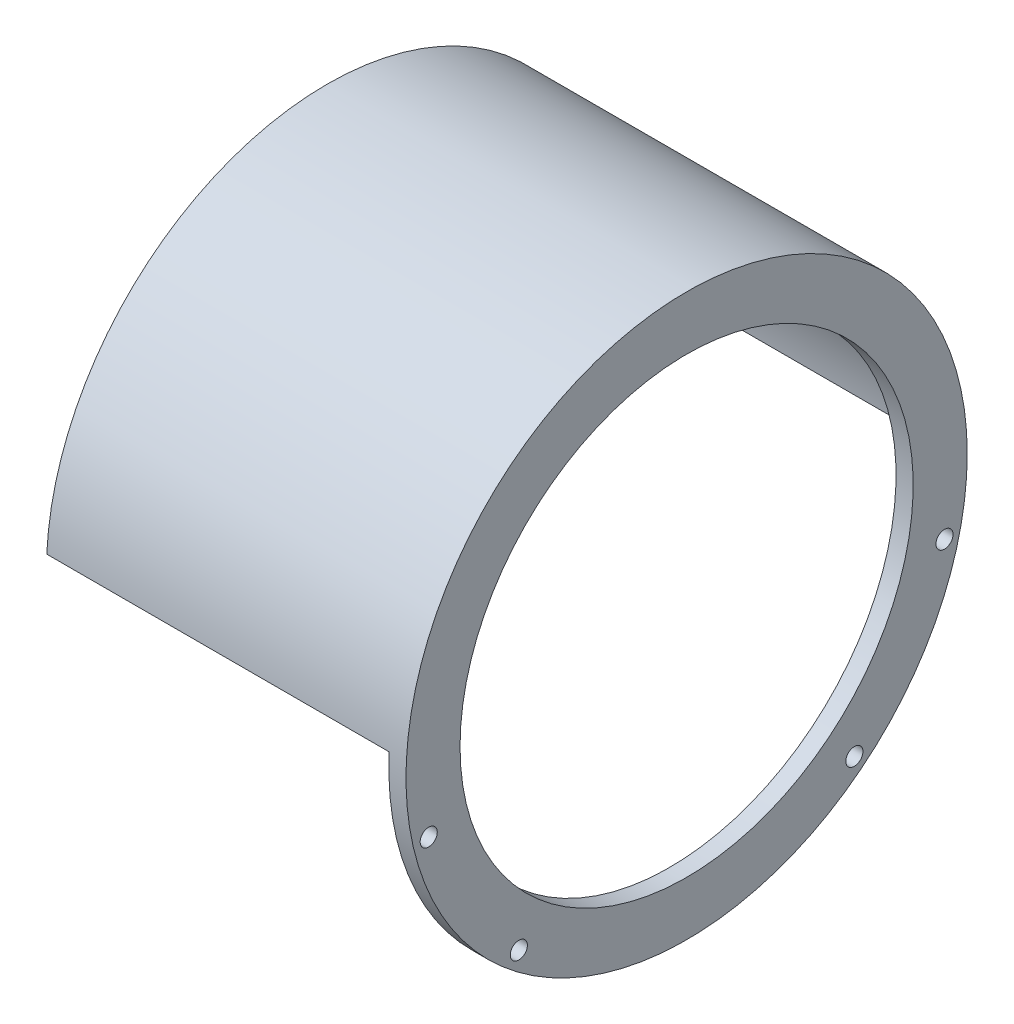
SolidWorks part; units mm, degrees
ref_plane "Спереди" through (0, 0, 0) normal (0, 0, 1) x (1, 0, 0)
ref_plane "Сверху" through (0, 0, 0) normal (0, 1, 0) x (1, 0, 0)
ref_plane "Справа" through (0, 0, 0) normal (1, 0, 0) x (0, 0, -1)
ref_plane "Плоскость4"
sketch "Эскиз1" plane through (0, 0, 0) normal (1, 0, 0) x (0, 1, 0)
  circle A0 centre (37.5, 47.7) radius 49.1718
  circle A1 centre (37.5, 47.7) radius 39.7
extrude "Выдавливание1" add sketch "Эскиз1" along normal blind 3 contours A0 A1
ref_plane "Плоскость5"
sketch "Эскиз2" plane through (0, 37.5, 47.7) normal (-1, 0, 0) x (0, 0, 1)
  arc A0 (-42.2878, 5.9187) -> (-49.1127, 2.4088) centre (0, -84.7) ccw
  arc A1 (42.2878, 5.9187) -> (-42.2878, 5.9187) centre (0, 0) ccw
  arc A2 (49.1127, 2.4088) -> (42.2878, 5.9187) centre (0, -84.7) ccw
  arc A3 (49.1127, 2.4088) -> (-49.1127, 2.4088) centre (0, 0) ccw
extrude "Выдавливание2" add sketch "Эскиз2" along normal blind 60
ref_plane "Плоскость6"
sketch "Эскиз3" plane through (3, 37.5, 47.7) normal (1, 0, 0) x (0, 0, -1)
  circle A0 centre (45.186, -10.976) radius 1.5
  circle A1 centre (29.3932, -36.0318) radius 1.5
  circle A2 centre (-29.3932, -36.0318) radius 1.5
  circle A3 centre (-45.186, -10.976) radius 1.5
  dimension "D1" = 3
  dimension "D2" = 3
extrude "Выдавливание4" cut sketch "Эскиз3" against normal blind 60 contours A0 | A1 | A2 | A3
ref_plane "Плоскость7"
sketch "Эскиз4" plane through (-60, 37.5, 47.7) normal (-1, 0, 0) x (0, 0, 1)
  line L0 (42.2878, 5.9187) -> (42.1214, 7.1077)
  line L1 (-42.1214, 7.1077) -> (-42.2878, 5.9187)
  line L2 (-0.25, 16.3089) -> (0.5, 16.308)
  line L3 (0.5, 16.308) -> (0, 16.3092)
  arc A0 (42.2878, 5.9187) -> (-42.2878, 5.9187) centre (0, -84.7) ccw
  arc A1 (42.1214, 7.1077) -> (-42.1214, 7.1077) centre (0, -84.7) ccw
  arc A2 (0, 16.3092) -> (-0.25, 16.3089) centre (0, -84.7) ccw
  dimension "D1" = 0.5
extrude "Выдавливание5" add sketch "Эскиз4" against normal blind 2 contours L3 A1 L2 | L0 A1 L2 L1 A0 | L3 A1
ref_plane "Плоскость8"
sketch "Эскиз5" plane through (1.5, 35.0974, 62.4739) normal (0, 1, 0) x (0, 0, -1)
  circle A0 centre (-31.1261, 51.234) radius 1.5
  circle A1 centre (-31.1261, 32.434) radius 1.5
  circle A2 centre (-31.1261, 14.694) radius 1.5
  circle A3 centre (60.6739, 51.234) radius 1.5
  circle A4 centre (60.6739, 32.434) radius 1.5
  circle A5 centre (60.6739, 14.694) radius 1.5
  dimension "D1" = 3
  dimension "D2" = 3
  dimension "D3" = 3
extrude "Резьба6" sketch "Эскиз5" blind 10 contours A0 | A1 | A2 | A3 | A4 | A5
cosmetic thread "Условное изображение резьбы1" parameters "D1"=4.2449, "D2"=0
cosmetic thread "Условное изображение резьбы2" parameters "D1"=4.2449, "D2"=0
cosmetic thread "Условное изображение резьбы3" parameters "D1"=4.2449, "D2"=0
cosmetic thread "Условное изображение резьбы4" parameters "D1"=4.2449, "D2"=0
cosmetic thread "Условное изображение резьбы5" parameters "D1"=4.2449, "D2"=0
cosmetic thread "Условное изображение резьбы6" parameters "D1"=4.2449, "D2"=0
